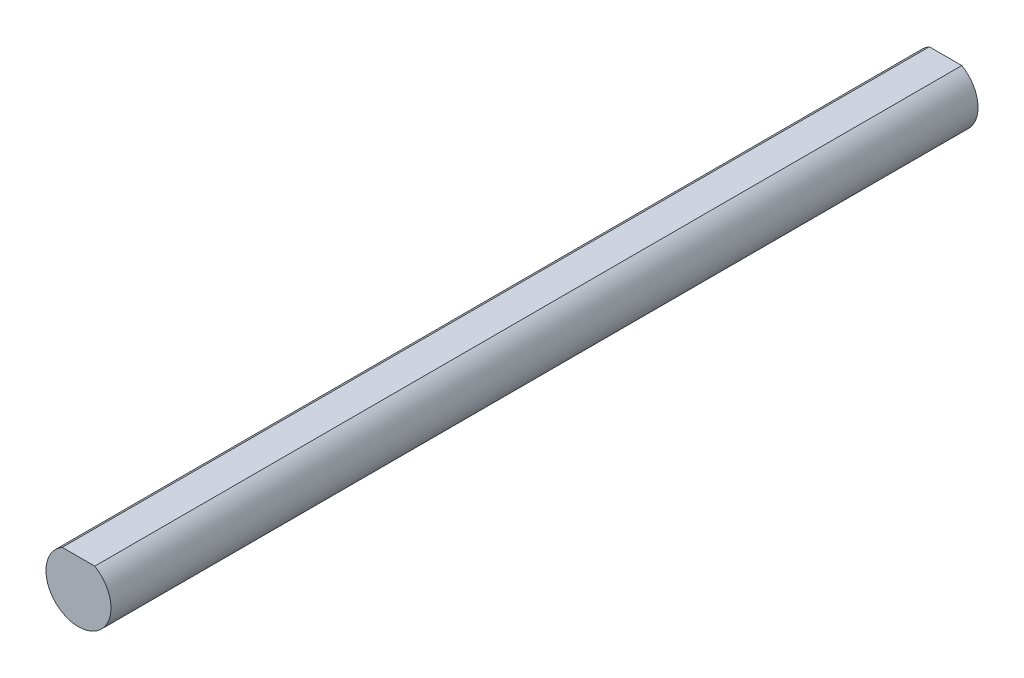
SolidWorks part; units mm, degrees
ref_plane "Front Plane" through (0, 0, 0) normal (0, 0, 1) x (1, 0, 0)
ref_plane "Top Plane" through (0, 0, 0) normal (0, 1, 0) x (1, 0, 0)
ref_plane "Right Plane" through (0, 0, 0) normal (1, 0, 0) x (0, 0, -1)
sketch "Sketch2" plane through (0, 0, 0) normal (0, 0, 1) x (1, 0, 0)
  line L0 (-1.5, 2.5981) -> (1.5, 2.5981)
  arc A0 (-1.5, 2.5981) -> (1.5, 2.5981) centre (0, 0) ccw
  dimension "D1" = 6
  dimension "D2" = 3
extrude "Boss-Extrude1" add sketch "Sketch2" along normal blind 80
